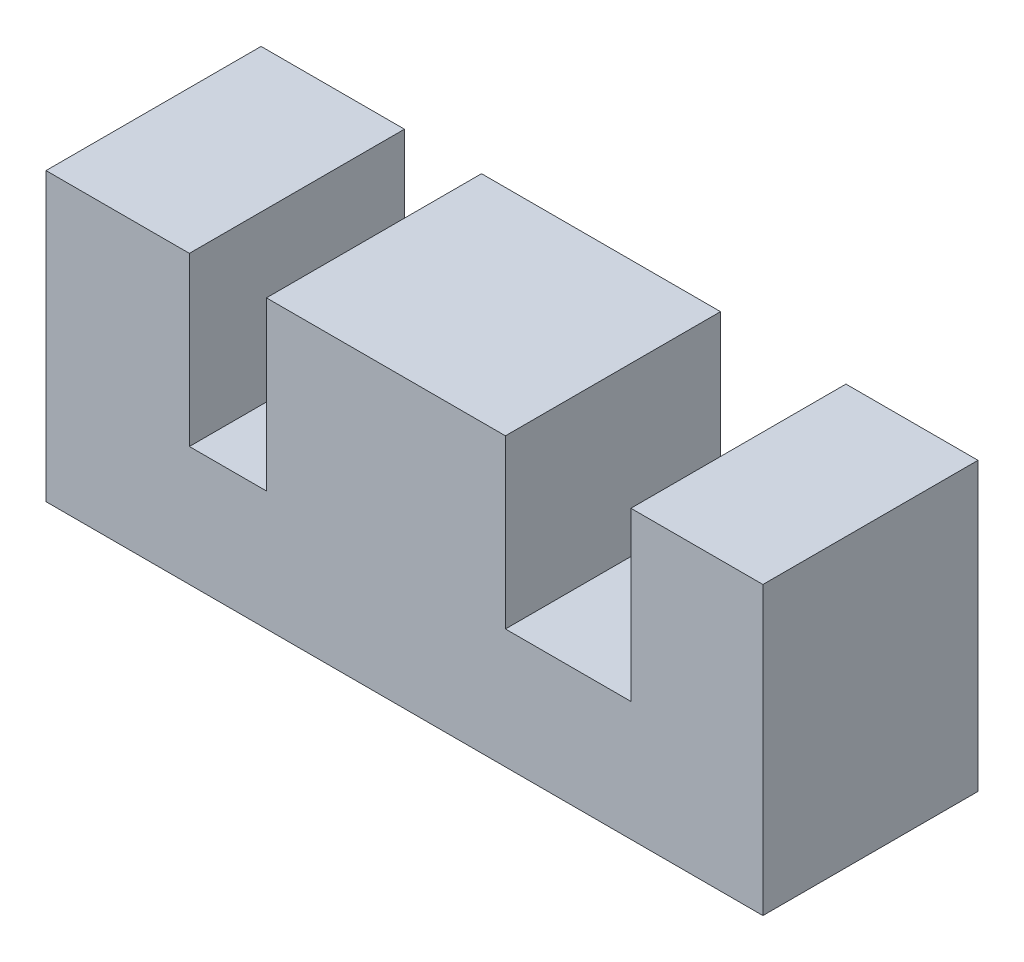
SolidWorks part; units mm, degrees
ref_plane "Front Plane" through (0, 0, 0) normal (0, 0, 1) x (1, 0, 0)
ref_plane "Top Plane" through (0, 0, 0) normal (0, 1, 0) x (1, 0, 0)
ref_plane "Right Plane" through (0, 0, 0) normal (1, 0, 0) x (0, 0, -1)
sketch "Sketch2" plane through (0, 0, 0) normal (0, 1, 0) x (1, 0, 0)
  line L1 (-36.9298, 9.7807) -> (23.0702, 9.7807)
  line L2 (-36.9298, 9.7807) -> (-36.9298, -8.2193)
  line L3 (-36.9298, -8.2193) -> (23.0702, -8.2193)
  line L4 (23.0702, 9.7807) -> (23.0702, -8.2193)
  dimension "D1" = 60
  dimension "D2" = 18
extrude "Boss-Extrude1" add sketch "Sketch2" along normal blind 10
sketch "Sketch3" plane through (0, 10, 0) normal (0, 1, 0) x (1, 0, 0)
  line L0 (23.0702, 9.7807) -> (-36.9298, 9.7807) construction
  line L1 (-36.9298, -8.2193) -> (-24.9298, -8.2193)
  line L2 (-36.9298, -8.2193) -> (-36.9298, 9.7807)
  line L3 (-36.9298, 9.7807) -> (-24.9298, 9.7807)
  line L4 (-24.9298, -8.2193) -> (-24.9298, 9.7807)
  line L5 (-36.9298, -8.2193) -> (23.0702, -8.2193) construction
  line L6 (1.5202, -8.2193) -> (-18.4798, -8.2193)
  line L7 (1.5202, -8.2193) -> (1.5202, 9.7807)
  line L8 (1.5202, 9.7807) -> (-18.4798, 9.7807)
  line L9 (-18.4798, -8.2193) -> (-18.4798, 9.7807)
  line L11 (23.0702, -8.2193) -> (12.0202, -8.2193)
  line L12 (23.0702, -8.2193) -> (23.0702, 9.7807)
  line L13 (23.0702, 9.7807) -> (12.0202, 9.7807)
  line L14 (12.0202, -8.2193) -> (12.0202, 9.7807)
  dimension "D1" = 20
  dimension "D2" = 10.5
  dimension "D3" = 6.45
  dimension "D4" = 12
extrude "Boss-Extrude2" add sketch "Sketch3" along normal blind 14
